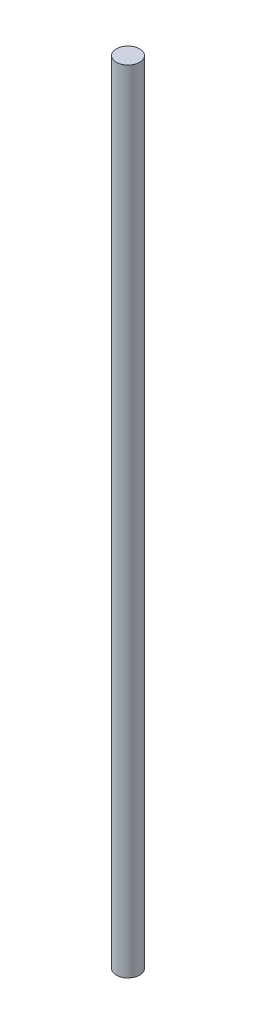
SolidWorks part; units mm, degrees
material "Nylon 101"
ref_plane "Alzado" through (0, 0, 0) normal (0, 0, 1) x (1, 0, 0)
ref_plane "Planta" through (0, 0, 0) normal (0, 1, 0) x (1, 0, 0)
ref_plane "Vista lateral" through (0, 0, 0) normal (1, 0, 0) x (0, 0, -1)
sketch "Sketch1" plane through (0, 0, 0) normal (0, 0, 1) x (1, 0, 0)
  line L0 (0, 0) -> (1.3, 0)
  line L1 (1.3, 0) -> (1.3, -88)
  line L2 (1.3, -88) -> (0, -88)
  line L3 (0, -88) -> (0, 0)
  line L4 (0, -92) -> (0, 4) construction
revolve "Tendon" add sketch "Sketch1" angle 360 about L4
